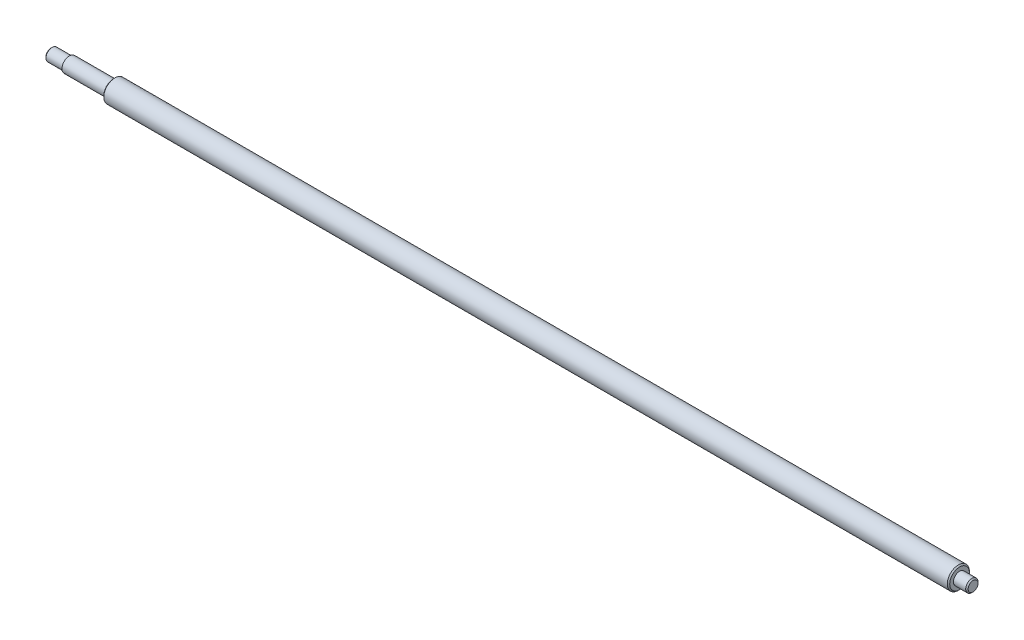
SolidWorks part; units mm, degrees
ref_plane "Front Plane" through (0, 0, 0) normal (0, 0, 1) x (1, 0, 0)
ref_plane "Top Plane" through (0, 0, 0) normal (0, 1, 0) x (1, 0, 0)
ref_plane "Right Plane" through (0, 0, 0) normal (1, 0, 0) x (0, 0, -1)
sketch "Sketch1" plane through (0, 0, 0) normal (0, 1, 0) x (1, 0, 0)
  line L0 (-222.9641, 0) -> (291.446, 0) construction
  line L1 (-208.4669, 0) -> (-208.4669, 4)
  line L2 (-207.4669, 5) -> (-193.4669, 5)
  line L3 (-193.4669, 5) -> (-193.4669, 6)
  line L4 (-193.4669, 6) -> (-157.4669, 6)
  line L5 (-157.4669, 6) -> (-157.4669, 8)
  line L6 (-156.4669, 9) -> (529.5331, 9)
  line L7 (530.5331, 8) -> (530.5331, 5)
  line L8 (530.5331, 5) -> (540.5331, 5)
  line L9 (541.5331, 4) -> (541.5331, 0)
  line L10 (-208.4669, 0) -> (541.5331, 0)
  line L11 (-208.4669, 4) -> (-207.4669, 5)
  line L12 (-157.4669, 8) -> (-156.4669, 9)
  line L13 (540.5331, 5) -> (541.5331, 4)
  line L14 (529.5331, 9) -> (530.5331, 8)
  point P4 (-208.4669, 5)
  point P9 (-157.4669, 9)
  point P10 (530.5331, 9)
  point P12 (541.5331, 5)
  dimension "D1" = 688
  dimension "D2" = 9
  dimension "D3" = 5
  dimension "D4" = 6
  dimension "D5" = 10
  dimension "D6" = 15
  dimension "D7" = 36
  dimension "D8" = 11
revolve "Revolve1" add sketch "Sketch1" angle 360 about L0
sketch "Szkic1" plane through (-208.4669, 0, 0) normal (-1, 0, 0) x (0, 0, 1)
  point P0 (0, 0)
